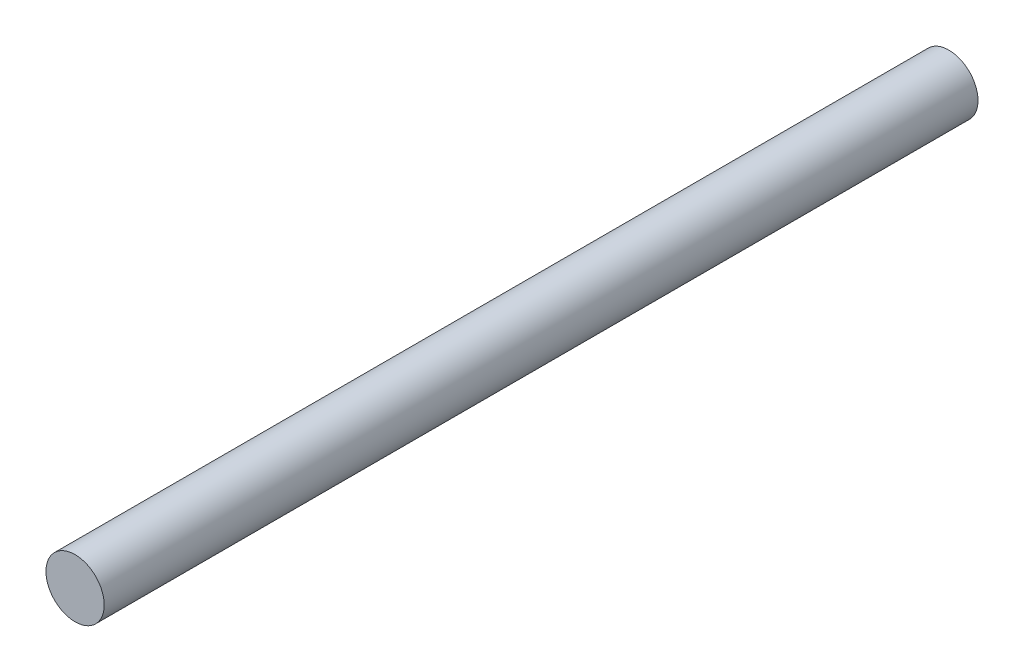
SolidWorks part; units mm, degrees
ref_plane "Alzado" through (0, 0, 0) normal (0, 0, 1) x (1, 0, 0)
ref_plane "Planta" through (0, 0, 0) normal (0, 1, 0) x (1, 0, 0)
ref_plane "Vista lateral" through (0, 0, 0) normal (1, 0, 0) x (0, 0, -1)
sketch "Croquis1" plane through (0, 0, 0) normal (0, 0, 1) x (1, 0, 0)
  circle A0 centre (0, 0) radius 4
  dimension "D1" = 8
extrude "Saliente-Extruir1" add sketch "Croquis1" along normal blind 120
